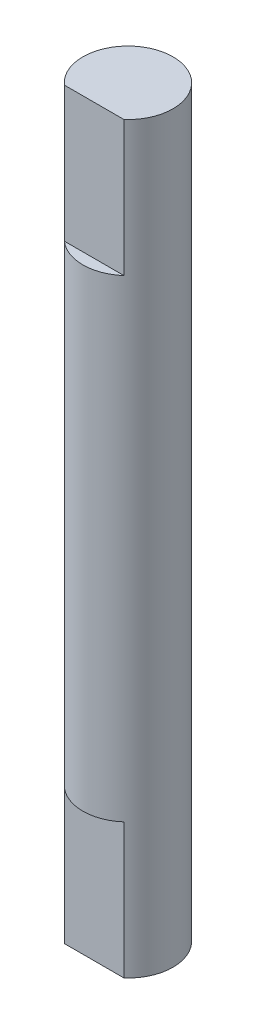
SolidWorks part; units mm, degrees
ref_plane "Front Plane" through (0, 0, 0) normal (0, 0, 1) x (1, 0, 0)
ref_plane "Top Plane" through (0, 0, 0) normal (0, 1, 0) x (1, 0, 0)
ref_plane "Right Plane" through (0, 0, 0) normal (1, 0, 0) x (0, 0, -1)
sketch "Sketch2" plane through (0, 0, 0) normal (0, 1, 0) x (1, 0, 0)
  circle A0 centre (0, 0) radius 4
  dimension "D1" = 8
extrude "Boss-Extrude2" add sketch "Sketch2" along normal blind 66
sketch "Sketch3" plane through (0, 66, 0) normal (0, 1, 0) x (1, 0, 0)
  line L0 (-2.6458, -3) -> (2.6458, -3)
  line L1 (0, -3) -> (0, 4) construction
  line L2 (0, -3) -> (0, -4) construction
  circle A2 centre (0, 0) radius 4
  arc A3 (-2.6458, -3) -> (2.6458, -3) centre (0, 0) ccw
  dimension "D2" = 7
  dimension "D3" = 1
  dimension "D1" = 0
extrude "Cut-Extrude1" cut sketch "Sketch3" against normal blind 12 contours L0 A3
sketch "Sketch4" plane through (0, 0, 0) normal (0, -1, 0) x (1, 0, 0)
  line L0 (-2.6458, 3) -> (2.6458, 3)
  line L1 (-4, 0) -> (2.8284, 0) construction
  line L2 (2.8284, 0) -> (4, 0) construction
  line L3 (0, -4) -> (0, 3) construction
  line L4 (0, 3) -> (0, 4) construction
  circle A2 centre (0, 0) radius 4
  arc A3 (4, 0) -> (-4, 0) centre (0, 0) ccw
  dimension "D2" = 7
  dimension "D3" = 1
  dimension "D1" = 0
extrude "Cut-Extrude3" cut sketch "Sketch4" against normal blind 12 and the other way through all contours L0
